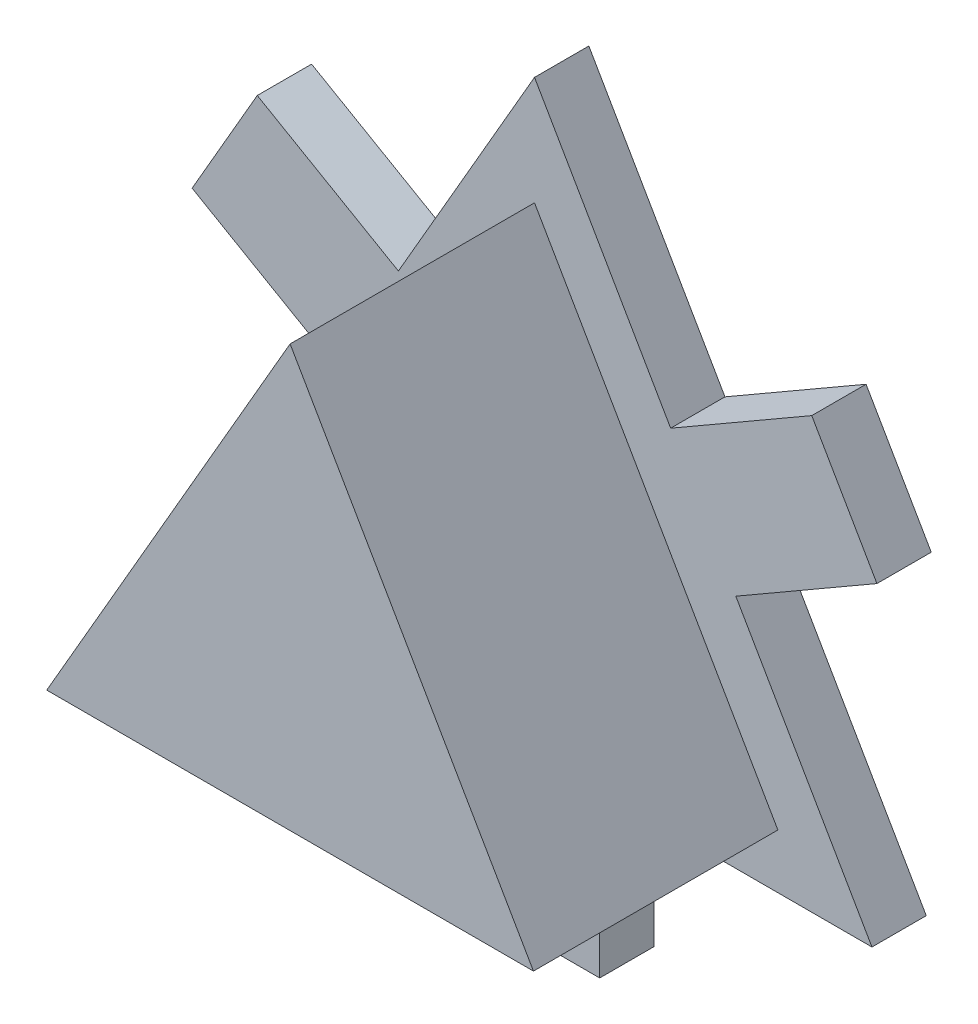
SolidWorks part; units mm, degrees
ref_plane "Front Plane" through (0, 0, 0) normal (0, 0, 1) x (1, 0, 0)
ref_plane "Top Plane" through (0, 0, 0) normal (0, 1, 0) x (1, 0, 0)
ref_plane "Right Plane" through (0, 0, 0) normal (1, 0, 0) x (0, 0, -1)
sketch "Sketch1" plane through (0, 0, 0) normal (0, 0, 1) x (1, 0, 0)
  line L9 (4.0328, -1.4984) -> (12.9936, -1.4984)
  line L10 (8.5132, 6.2619) -> (4.0328, -1.4984)
  line L11 (12.9936, -1.4984) -> (8.5132, 6.2619)
  line L12 (4.0328, -1.4984) -> (12.9936, -1.4984)
  line L13 (8.5132, 6.2619) -> (4.0328, -1.4984)
  line L14 (12.9936, -1.4984) -> (8.5132, 6.2619)
  circle A0 centre (8.5132, 1.0884) radius 2.5868 construction
  dimension "D1" = 0.3
extrude "Boss-Extrude1" add sketch "Sketch1" along normal blind 4.5
sketch "Sketch2" plane through (0, 0, 0) normal (0, 0, -1) x (-1, 0, 0)
  line L36 (-14.8175, 3.3425) -> (-12.2194, 1.8425)
  line L37 (-12.2194, 1.8425) -> (-14.7256, -2.4984)
  line L38 (-14.7256, -2.4984) -> (-9.7132, -2.4984)
  line L39 (-9.7132, -2.4984) -> (-9.7132, -5.4984)
  line L40 (-9.7132, -5.4984) -> (-7.3132, -5.4984)
  line L41 (-7.3132, -5.4984) -> (-7.3132, -2.4984)
  line L42 (-7.3132, -2.4984) -> (-2.3008, -2.4984)
  line L43 (-2.3008, -2.4984) -> (-4.807, 1.8425)
  line L44 (-4.807, 1.8425) -> (-2.2089, 3.3425)
  line L45 (-2.2089, 3.3425) -> (-3.4089, 5.421)
  line L46 (-3.4089, 5.421) -> (-6.007, 3.921)
  line L47 (-6.007, 3.921) -> (-8.5132, 8.2619)
  line L48 (-8.5132, 8.2619) -> (-11.0194, 3.921)
  line L49 (-11.0194, 3.921) -> (-13.6175, 5.421)
  line L50 (-13.6175, 5.421) -> (-14.8175, 3.3425)
  line L51 (-14.8175, 3.3425) -> (-12.2194, 1.8425)
  line L52 (-12.2194, 1.8425) -> (-14.7256, -2.4984)
  line L53 (-14.7256, -2.4984) -> (-9.7132, -2.4984)
  line L54 (-9.7132, -2.4984) -> (-9.7132, -5.4984)
  line L55 (-9.7132, -5.4984) -> (-7.3132, -5.4984)
  line L56 (-7.3132, -5.4984) -> (-7.3132, -2.4984)
  line L57 (-7.3132, -2.4984) -> (-2.3008, -2.4984)
  line L58 (-2.3008, -2.4984) -> (-4.807, 1.8425)
  line L59 (-4.807, 1.8425) -> (-2.2089, 3.3425)
  line L60 (-2.2089, 3.3425) -> (-3.4089, 5.421)
  line L61 (-3.4089, 5.421) -> (-6.007, 3.921)
  line L62 (-6.007, 3.921) -> (-8.5132, 8.2619)
  line L63 (-8.5132, 8.2619) -> (-11.0194, 3.921)
  line L64 (-11.0194, 3.921) -> (-13.6175, 5.421)
  line L65 (-13.6175, 5.421) -> (-14.8175, 3.3425)
  dimension "D1" = 0.3
extrude "Boss-Extrude2" add sketch "Sketch2" along normal blind 1
